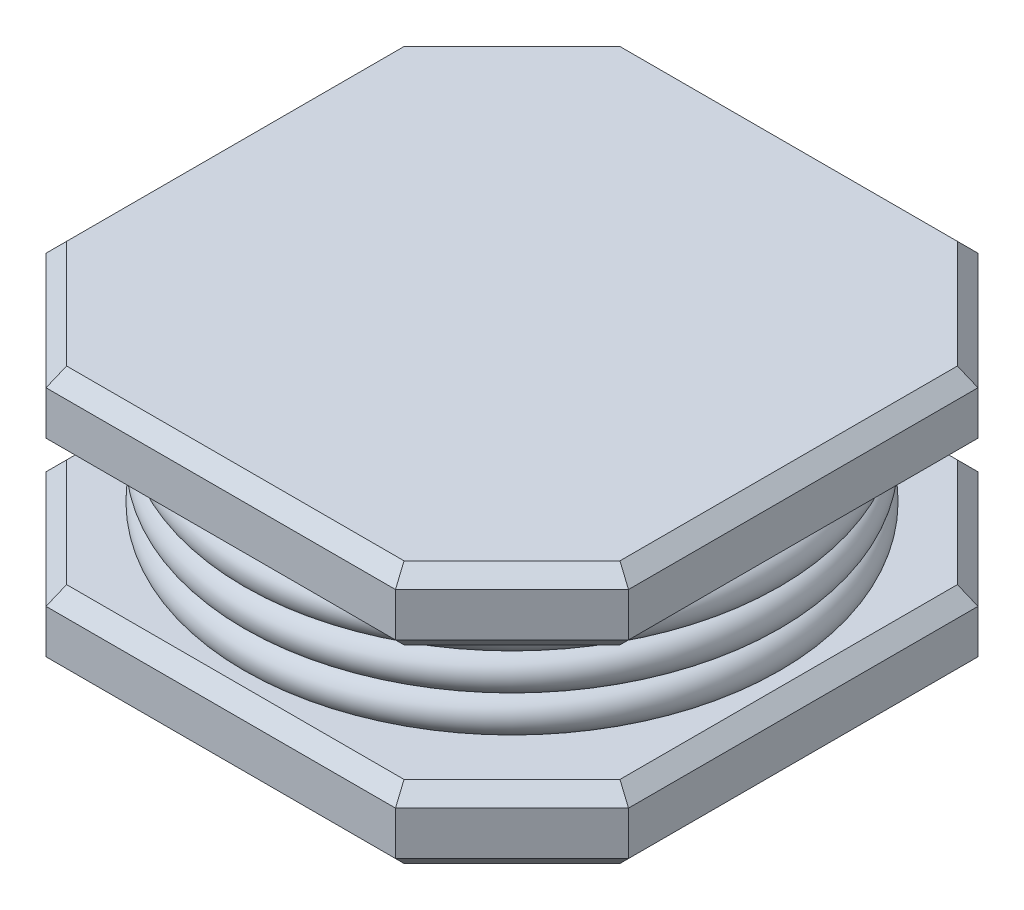
SolidWorks part; units mm, degrees
ref_plane "Front Plane" through (0, 0, 0) normal (0, 0, 1) x (1, 0, 0)
ref_plane "Top Plane" through (0, 0, 0) normal (0, 1, 0) x (1, 0, 0)
ref_plane "Right Plane" through (0, 0, 0) normal (1, 0, 0) x (0, 0, -1)
sketch "BaseS" plane through (0, 0, 0) normal (0, 1, 0) x (1, 0, 0)
  line L1 (-2, -2) -> (2, -2)
  line L2 (-2, -2) -> (-2, 2)
  line L3 (-2, 2) -> (2, 2)
  line L4 (2, -2) -> (2, 2)
  line L5 (-2, -2) -> (2, 2) construction
  line L6 (-2, 2) -> (2, -2) construction
  point P0 (0, 0)
  dimension "Length" = 4
extrude "Base" add sketch "BaseS" along normal blind 0.5
sketch "CoilEncasementS" plane through (0, 0.5, 0) normal (0, 1, 0) x (1, 0, 0)
  circle A0 centre (0, 0) radius 1.5
  dimension "D1" = 3
extrude "CoilEncasement" add sketch "CoilEncasementS" along normal blind 0.8
sketch "TopBaseS" plane through (0, 1.3, 0) normal (0, 1, 0) x (1, 0, 0)
  line L1 (-2, 2) -> (2, 2)
  line L2 (-2, 2) -> (-2, -2)
  line L3 (-2, -2) -> (2, -2)
  line L4 (2, 2) -> (2, -2)
  line L5 (-2, 2) -> (2, -2) construction
  line L6 (-2, -2) -> (2, 2) construction
  dimension "Length" = 4
extrude "TopBase" add sketch "TopBaseS" along normal blind 0.5
ref_plane "CoilStart" through (0, 0.625, 0) normal (0, 1, 0) x (1, 0, 0)
sketch "CoilS" plane through (0, 0.625, 0) normal (0, 1, 0) x (1, 0, 0)
  circle A0 centre (0, 0) radius 1.75
  dimension "D1" = 3.5
sweep "Coil" add path "CoilS" circular profile diameter 0.25 parameters "D3"=0.25
pattern_linear "COIL P" count 3 spacing 0.25 along (0, 1, 0) of "Coil"
chamfer "Chamfer1" distance 0.8 angle 45 8 edges at (2, 0.25, -2) (-2, 0.25, -2) (-2, 0.25, 2) (2, 0.25, 2) (2, 1.55, -2) (-2, 1.55, -2) (-2, 1.55, 2) (2, 1.55, 2)
chamfer "BASES C" distance 0.1 angle 45 34 edges at (0, 0.5, -1.5) (0, 1.8, 2) (-2, 1.8, 0) (0, 1.8, -2) (2, 1.8, 0) (0, 0, -2) (-2, 0, 0) (0, 0, 2) (2, 0, 0) (0, 0.5, 2) (-2, 0.5, 0) (0, 0.5, -2) (2, 0.5, 0) (0, 1.3, -2) (-2, 1.3, 0) (0, 1.3, 2) (2, 1.3, 0) (0, 1.3, 1.5) (-1.6, 1.3, -1.6) (-1.6, 1.3, 1.6) (1.6, 1.3, 1.6) (1.6, 1.3, -1.6) (1.6, 1.8, 1.6) (-1.6, 1.8, 1.6) (-1.6, 1.8, -1.6) (1.6, 1.8, -1.6) (-1.6, 0, -1.6) (-1.6, 0, 1.6) (1.6, 0, 1.6) (1.6, 0, -1.6) (1.6, 0.5, 1.6) (-1.6, 0.5, 1.6) (-1.6, 0.5, -1.6) (1.6, 0.5, -1.6)
equation "\"Height@TopBase\" = \"Height@Base\""
